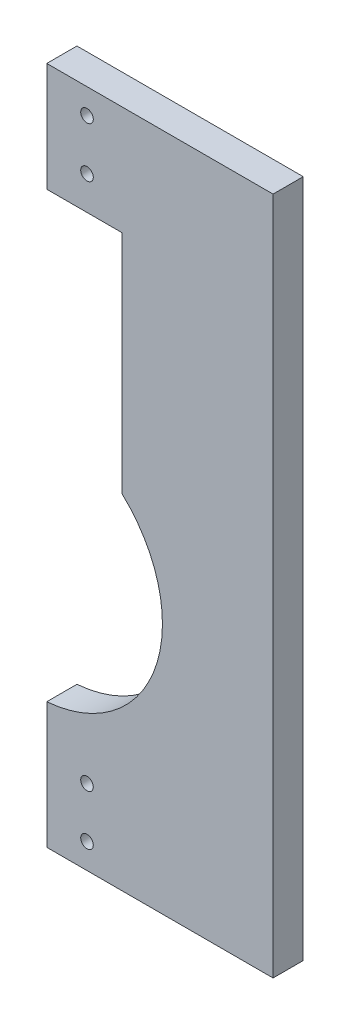
SolidWorks part; units mm, degrees
ref_plane "Plan de face" through (0, 0, 0) normal (0, 0, 1) x (1, 0, 0)
ref_plane "Plan de dessus" through (0, 0, 0) normal (0, 1, 0) x (1, 0, 0)
ref_plane "Plan de droite" through (0, 0, 0) normal (1, 0, 0) x (0, 0, -1)
sketch "Esquisse1" plane through (0, 0, 0) normal (0, 0, 1) x (1, 0, 0)
  line L0 (45, 67.5) -> (0, 67.5) construction
  line L1 (0, 0) -> (45, 0)
  line L2 (0, 0) -> (0, 135)
  line L3 (0, 135) -> (45, 135)
  line L4 (45, 0) -> (45, 135)
  circle A0 centre (8, 5) radius 1.25
  circle A1 centre (8, 15) radius 1.25
  circle A2 centre (8, 120) radius 1.25
  circle A3 centre (8, 130) radius 1.25
  point P7 (0, 0)
  dimension "D3" = 5
  dimension "D1" = 45
  dimension "D2" = 135
  dimension "D5" = 8
  dimension "D4" = 2
extrude "Boss.-Extru.1" add sketch "Esquisse1" along normal blind 6
sketch "Esquisse2" plane through (0, 0, 0) normal (0, 0, -1) x (-1, 0, 0)
  line L0 (0, 135) -> (0, 0) construction
  line L1 (0, 25.0801) -> (0, 113.3303)
  line L2 (0, 113.3303) -> (-15, 113.3303)
  line L3 (-15, 113.3303) -> (-15, 68.3303)
  line L4 (0, 0) -> (-45, 0) construction
  arc A0 (0, 25.0801) -> (-15, 68.3303) centre (2, 50) cw
  dimension "D1" = 25
  dimension "D2" = 50
  dimension "D3" = 45
  dimension "D4" = 15
  dimension "D5" = 2
extrude "Enlèv. mat.-Extru.1" cut sketch "Esquisse2" against normal through all
